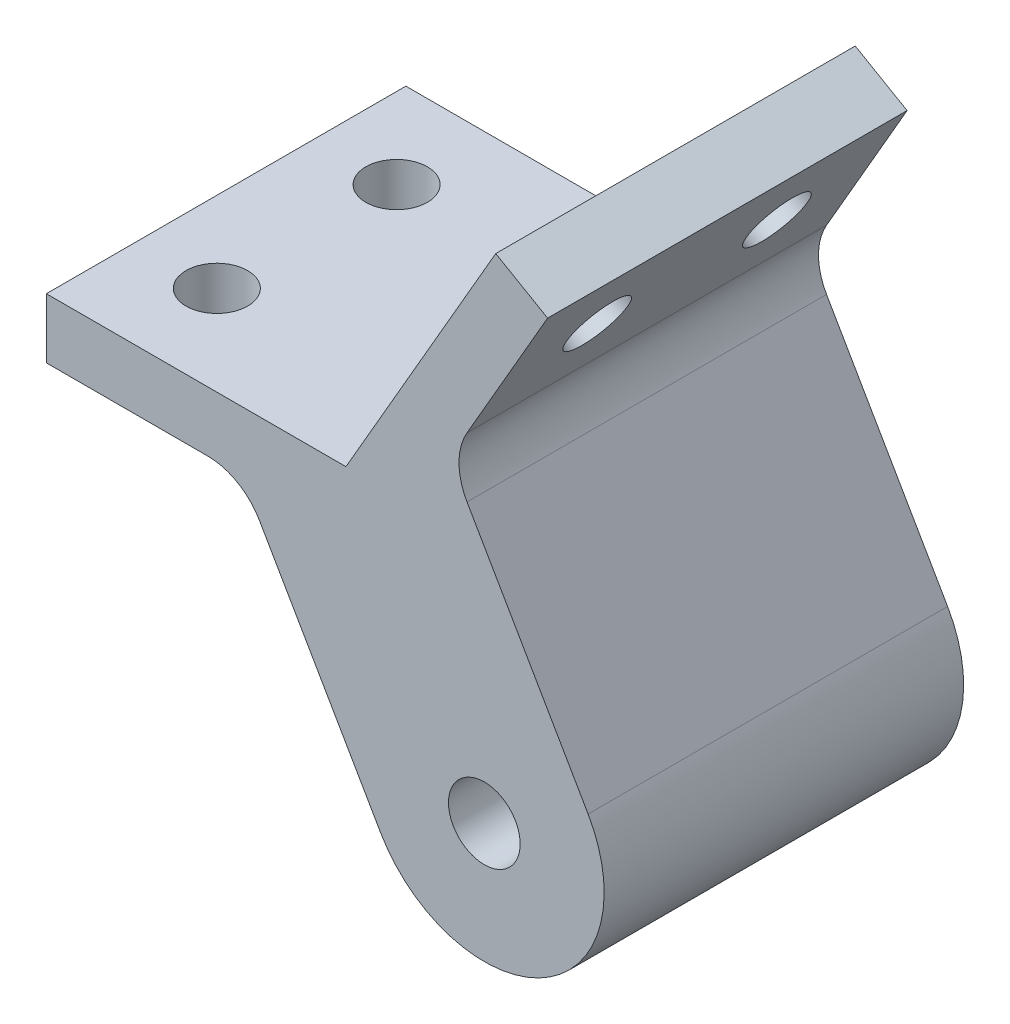
SolidWorks part; units mm, degrees
material "Custom Plastic"
ref_plane "Front Plane" through (0, 0, 0) normal (0, 0, 1) x (1, 0, 0)
ref_plane "Top Plane" through (0, 0, 0) normal (0, 1, 0) x (1, 0, 0)
ref_plane "Right Plane" through (0, 0, 0) normal (1, 0, 0) x (0, 0, -1)
sketch "Sketch1" plane through (0, 0, 0) normal (0, 0, 1) x (1, 0, 0)
  line L0 (0, 0) -> (-14.6647, 0) construction
  line L1 (-14.6647, 0) -> (-7.3323, 12.7) construction
  line L2 (-7.3323, 12.7) -> (7.3323, 12.7) construction
  line L3 (7.3323, 12.7) -> (0, 0) construction
  line L4 (-7.3323, 12.7) -> (0.6052, 26.4482)
  line L5 (-7.3323, 12.7) -> (-23.2073, 12.7)
  line L6 (-23.2073, 12.7) -> (-23.2073, 9.525)
  line L7 (0.6052, 26.4482) -> (3.3548, 24.8607)
  line L8 (-5.4993, -3.175) -> (-12.8316, 9.525)
  line L9 (5.4993, 3.175) -> (-1.8331, 15.875)
  line L10 (0, 0) -> (-7.3323, 12.7) construction
  line L11 (-23.2073, 9.525) -> (-12.8316, 9.525)
  line L12 (3.3548, 24.8607) -> (-1.8331, 15.875)
  arc A0 (-5.4993, -3.175) -> (5.4993, 3.175) centre (0, 0) ccw
  dimension "D8" = 12.7
  dimension "D1" = 120
  dimension "D2" = 12.7
  dimension "D3" = 12.7
  dimension "D4" = 15.875
  dimension "D5" = 15.875
  dimension "D6" = 3.175
  dimension "D7" = 3.175
extrude "Boss-Extrude1" add sketch "Sketch1" along normal blind 19.05
hole_wizard "#6 Clearance Hole1" positions "3DSketch2" profile "Sketch4" hole size "#6" standard "ANSI Inch" end condition through all
sketch3d "3DSketch2"
  point P0 (0, 0, 0)
sketch "Sketch4" plane through (0, 0, 0) normal (1, 0, 0) x (0, 1, 0)
  line L0 (0, 0) -> (0, 19.05)
  line L1 (0, 19.05) -> (1.8986, 19.05)
  line L2 (1.8986, 19.05) -> (1.8986, 0)
  line L5 (1.8986, 0) -> (0, 0)
  line L11 (0, -6.35) -> (0, 107.95) construction
  dimension "Thru Hole Dia." = 3.7973
  dimension "Thru Hole Depth" = 19.05
fillet "Fillet1" radius 3.175 2 edges at (-12.8316, 9.525, 9.525) (-1.8331, 15.875, 9.525)
hole_wizard "E (0.25) Diameter Hole1" positions "Sketch7" profile "Sketch8" hole size "E" standard "ANSI Inch" end condition through all
sketch "Sketch7" plane through (-8.2489, 4.7625, 0) normal (0.866, -0.5, 0) x (0, 0, -1)
  line L0 (-19.05, 18.936) -> (0, 18.936) construction
  line L1 (-19.05, 14.6647) -> (-19.05, 23.2073) construction
  line L2 (0, 14.6647) -> (0, 23.2073) construction
  line L8 (-9.525, 23.2073) -> (-9.525, 14.6647) construction
  line L9 (-19.05, 23.2073) -> (0, 23.2073) construction
  line L10 (-19.05, 14.6647) -> (0, 14.6647) construction
  point P19 (-14.2875, 18.936)
  point P21 (-4.7625, 18.936)
  dimension "D1" = 9.525
sketch "Sketch8" plane through (1.2191, 21.1616, 4.7625) normal (0, 0, 1) x (0.5, 0.866, 0)
  line L0 (0, 0) -> (0, 23.7972)
  line L1 (0, 23.7972) -> (1.6319, 23.7972)
  line L2 (1.6319, 23.7972) -> (1.6319, 0)
  line L5 (1.6319, 0) -> (0, 0)
  line L11 (0, -6.35) -> (0, 107.95) construction
  dimension "Thru Hole Dia." = 3.2639
  dimension "Thru Hole Depth" = 23.7972
hole_wizard "E (0.25) Diameter Hole2" positions "3DSketch3" profile "Sketch9" hole size "E" standard "ANSI Inch" end condition through all
sketch3d "3DSketch3"
  line L0 (-18.936, 9.525, 0) -> (-18.936, 9.525, 19.05) construction
  line L1 (-23.2073, 9.525, 0) -> (-14.6647, 9.525, 0) construction
  line L2 (-23.2073, 9.525, 19.05) -> (-14.6647, 9.525, 19.05) construction
  line L7 (-23.2073, 9.525, 9.525) -> (-14.6647, 9.525, 9.525) construction
  line L8 (-23.2073, 9.525, 19.05) -> (-23.2073, 9.525, 0) construction
  line L9 (-14.6647, 9.525, 0) -> (-14.6647, 9.525, 19.05) construction
  point P17 (-18.936, 9.525, 4.7625)
  point P19 (-18.936, 9.525, 14.2875)
  dimension "D1" = 9.525
sketch "Sketch9" plane through (-18.936, 9.525, 14.2875) normal (1, 0, 0) x (0, 0, -1)
  line L0 (0, 0) -> (0, 16.9232)
  line L1 (0, 16.9232) -> (1.6319, 16.9232)
  line L2 (1.6319, 16.9232) -> (1.6319, 0)
  line L5 (1.6319, 0) -> (0, 0)
  line L11 (0, -6.35) -> (0, 107.95) construction
  dimension "Thru Hole Dia." = 3.2639
  dimension "Thru Hole Depth" = 16.9232
equation "\"D5@Sketch1\"=\"D4@Sketch1\""
equation "\"D7@Sketch1\"=\"D6@Sketch1\""
equation "\"D2@Sketch1\"=\"D3@Sketch1\""
equation "\"D1@3DSketch3\"=\"D1@Sketch7\""
